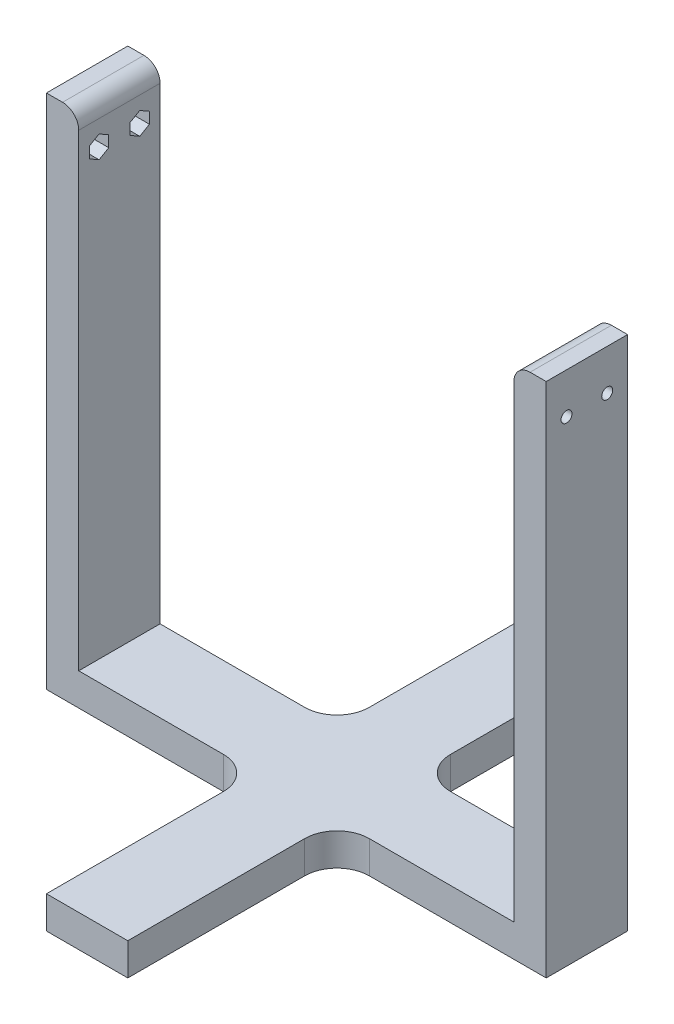
SolidWorks part; units mm, degrees
ref_plane "Front Plane" through (0, 0, 0) normal (0, 0, 1) x (1, 0, 0)
ref_plane "Top Plane" through (0, 0, 0) normal (0, 1, 0) x (1, 0, 0)
ref_plane "Right Plane" through (0, 0, 0) normal (1, 0, 0) x (0, 0, -1)
sketch "Sketch1" plane through (0, 0, 0) normal (0, 1, 0) x (1, 0, 0)
  line L0 (12.6, 12.6) -> (77.4, 12.6)
  line L1 (-12.6, 77.4) -> (12.6, 77.4)
  line L2 (-12.6, 77.4) -> (-12.6, 12.6)
  line L3 (-12.6, -77.4) -> (12.6, -77.4)
  line L4 (12.6, 77.4) -> (12.6, 12.6)
  line L5 (-12.6, 77.4) -> (12.6, -77.4) construction
  line L6 (-12.6, -77.4) -> (12.6, 77.4) construction
  line L7 (-77.4, 12.6) -> (-12.6, 12.6)
  line L8 (-77.4, 12.6) -> (-77.4, -12.6)
  line L9 (-77.4, -12.6) -> (-12.6, -12.6)
  line L10 (77.4, 12.6) -> (77.4, -12.6)
  line L11 (-77.4, 12.6) -> (77.4, -12.6) construction
  line L12 (-77.4, -12.6) -> (77.4, 12.6) construction
  line L13 (12.6, -12.6) -> (77.4, -12.6)
  line L14 (12.6, -12.6) -> (12.6, -77.4)
  line L15 (-12.6, -12.6) -> (-12.6, -77.4)
  point P0 (0, 0)
  point P5 (0, 0)
  dimension "D1" = 154.8
  dimension "D2" = 154.8
  dimension "D3" = 25.2
  dimension "D4" = 25.2
extrude "Boss-Extrude1" add sketch "Sketch1" along normal blind 10
sketch "Sketch2" plane through (0, 10, 0) normal (0, 1, 0) x (1, 0, 0)
  line L0 (77.4, -12.6) -> (77.4, 12.6) construction
  line L1 (67.4, 12.6) -> (77.4, 12.6)
  line L2 (67.4, 12.6) -> (67.4, -12.6)
  line L3 (67.4, -12.6) -> (77.4, -12.6)
  line L4 (77.4, 12.6) -> (77.4, -12.6)
  line L5 (67.4, 12.6) -> (77.4, -12.6) construction
  line L6 (67.4, -12.6) -> (77.4, 12.6) construction
  point P0 (72.4, 0)
  dimension "D1" = 25.2
  dimension "D2" = 10
  dimension "D3" = 0
extrude "Boss-Extrude2" add sketch "Sketch2" along normal blind 150
sketch "Sketch3" plane through (77.4, 0, 0) normal (1, 0, 0) x (0, 0, -1)
  line L0 (-12.6, 160) -> (-12.6, 134.8) construction
  line L1 (-12.6, 160) -> (-12.6, 0) construction
  line L2 (-12.6, 147.4) -> (0, 147.4) construction
  line L3 (0, 147.4) -> (0, 153.1943) construction
  circle A0 centre (-6.3, 147.4) radius 1.7
  circle A1 centre (6.3, 147.4) radius 1.7
  dimension "D1" = 3.4
extrude "Cut-Extrude1" cut sketch "Sketch3" against normal through all
sketch "Sketch4" plane through (67.4, 0, 0) normal (-1, 0, 0) x (0, 0, 1)
  line L0 (0, 146.8811) -> (0, 155.2788) construction
  line L1 (-6.3, 143.9359) -> (-3.3, 145.6679)
  line L2 (-3.3, 145.6679) -> (-3.3, 149.1321)
  line L3 (-3.3, 149.1321) -> (-6.3, 150.8641)
  line L4 (-6.3, 150.8641) -> (-9.3, 149.1321)
  line L5 (-9.3, 149.1321) -> (-9.3, 145.6679)
  line L6 (-9.3, 145.6679) -> (-6.3, 143.9359)
  line L7 (9.3, 145.6679) -> (6.3, 143.9359)
  line L8 (9.3, 149.1321) -> (9.3, 145.6679)
  line L9 (6.3, 150.8641) -> (9.3, 149.1321)
  line L10 (3.3, 149.1321) -> (6.3, 150.8641)
  line L11 (3.3, 145.6679) -> (3.3, 149.1321)
  line L12 (6.3, 143.9359) -> (3.3, 145.6679)
  circle A0 centre (-6.3, 147.4) radius 3 construction
  circle A1 centre (6.3, 147.4) radius 3 construction
  dimension "D1" = 6
extrude "Cut-Extrude2" cut sketch "Sketch4" against normal blind 5
mirror "Mirror1" about plane through (0, 0, 0) normal (1, 0, 0) of "Boss-Extrude2", "Cut-Extrude1", "Cut-Extrude2"
fillet "Fillet1" radius 10 4 edges at (12.6, 5, 12.6) (-12.6, 5, 12.6) (-12.6, 5, -12.6) (12.6, 5, -12.6)
fillet "Fillet2" radius 5 2 edges at (67.4, 160, 0) (-67.4, 160, 0)
